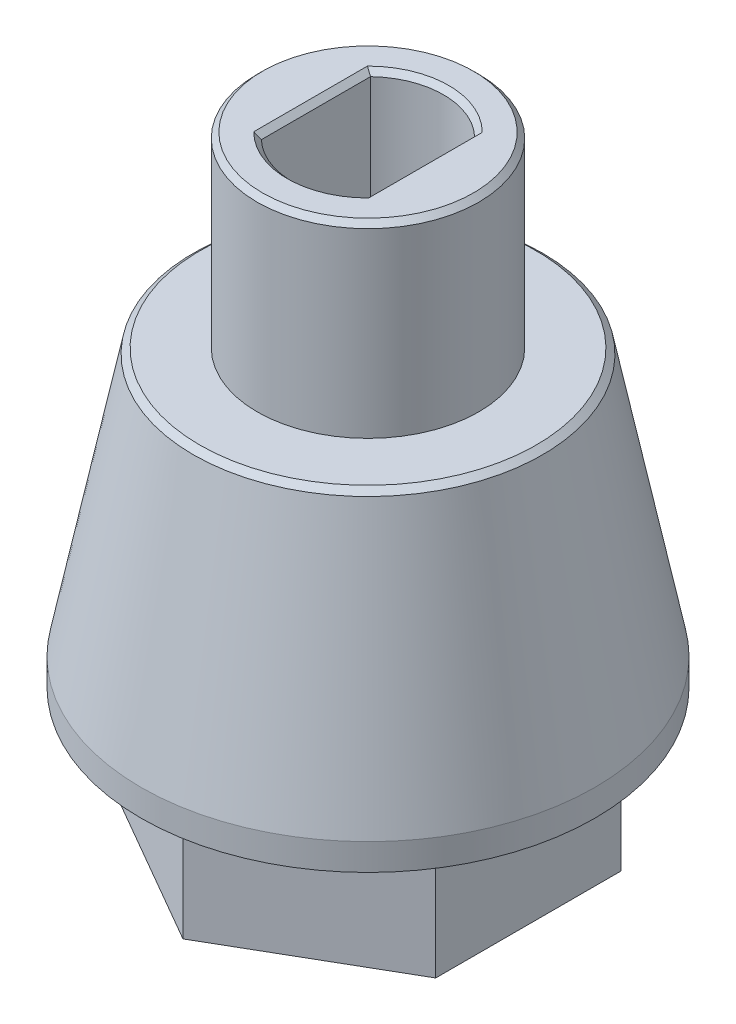
SolidWorks part; units mm, degrees
ref_plane "Front Plane" through (0, 0, 0) normal (0, 0, 1) x (1, 0, 0)
ref_plane "Top Plane" through (0, 0, 0) normal (0, 1, 0) x (1, 0, 0)
ref_plane "Right Plane" through (0, 0, 0) normal (1, 0, 0) x (0, 0, -1)
sketch "Sketch1" plane through (0, 0, 0) normal (0, 1, 0) x (1, 0, 0)
  line L0 (0, 6.9282) -> (0, -6.9282) construction
  line L1 (-6, -3.4641) -> (6, 3.4641) construction
  line L2 (6, -3.4641) -> (-6, 3.4641) construction
  line L3 (0, 6.9282) -> (6, 3.4641)
  line L4 (6, 3.4641) -> (6, -3.4641)
  line L5 (6, -3.4641) -> (0, -6.9282)
  line L6 (0, -6.9282) -> (-6, -3.4641)
  line L7 (-6, -3.4641) -> (-6, 3.4641)
  line L8 (-6, 3.4641) -> (0, 6.9282)
  dimension "D1" = 60
  dimension "D2" = 60
  dimension "D3" = 12
extrude "Boss-Extrude1" add sketch "Sketch1" along normal blind 4.7
sketch "Sketch2" plane through (0, 4.7, 0) normal (0, 1, 0) x (1, 0, 0)
  circle A0 centre (0, 0) radius 8.5
  dimension "D1" = 17
extrude "Boss-Extrude2" add sketch "Sketch2" along normal blind 1
sketch "Sketch3" plane through (0, 5.7, 0) normal (0, 1, 0) x (1, 0, 0)
  circle A0 centre (0, 0) radius 8.5
  circle A1 centre (0, 0) radius 8.5 construction
ref_plane "Plane1" through (0, 15.7, 0) normal (0, 1, 0) x (1, 0, 0)
sketch "Sketch4" plane through (0, 15.7, 0) normal (0, 1, 0) x (1, 0, 0)
  circle A0 centre (0, 0) radius 6.5
  dimension "D1" = 13
loft "Loft1" add profiles "Sketch4", "Sketch3"
sketch "Sketch5" plane through (0, 15.7, 0) normal (0, 1, 0) x (1, 0, 0)
  line L0 (-1.95, 2.044) -> (-1.95, -2.044)
  line L1 (1.95, 2.044) -> (1.95, -2.044)
  circle A0 centre (0, 0) radius 4.15
  arc A1 (-1.95, -2.044) -> (1.95, -2.044) centre (0, 0) ccw
  arc A2 (1.95, 2.044) -> (-1.95, 2.044) centre (0, 0) ccw
  dimension "D1" = 8.3
  dimension "D2" = 5.65
  dimension "D3" = 3.9
extrude "Boss-Extrude3" add sketch "Sketch5" along normal blind 7
chamfer "Chamfer1" distance 0.2 6 edges at (-1.95, 22.7, 0) (0, 22.7, -2.825) (1.95, 22.7, 0) (0, 22.7, 2.825) (0, 22.7, 4.15) (0, 15.7, 6.5)
sketch "Sketch6" plane through (0, 0, 0) normal (0, -1, 0) x (1, 0, 0)
  circle A0 centre (0, 0) radius 0.75
  dimension "D1" = 1.5
extrude "Cut-Extrude1" cut sketch "Sketch6" against normal blind 7
sketch "Sketch7" plane through (0, 15.7, 0) normal (0, 1, 0) x (1, 0, 0)
  line L8 (1.95, -2.044) -> (1.95, 2.044)
  line L9 (-1.95, 2.044) -> (-1.95, -2.044)
  line L10 (1.95, -2.044) -> (1.95, 2.044)
  line L11 (-1.95, 2.044) -> (-1.95, -2.044)
  arc A6 (1.95, 2.044) -> (-1.95, 2.044) centre (0, 0) ccw
  arc A7 (-1.95, -2.044) -> (1.95, -2.044) centre (0, 0) ccw
  arc A8 (1.95, 2.044) -> (-1.95, 2.044) centre (0, 0) ccw
  arc A9 (-1.95, -2.044) -> (1.95, -2.044) centre (0, 0) ccw
  dimension "D1" = 0
extrude "Cut-Extrude2" cut sketch "Sketch7" against normal blind 1
